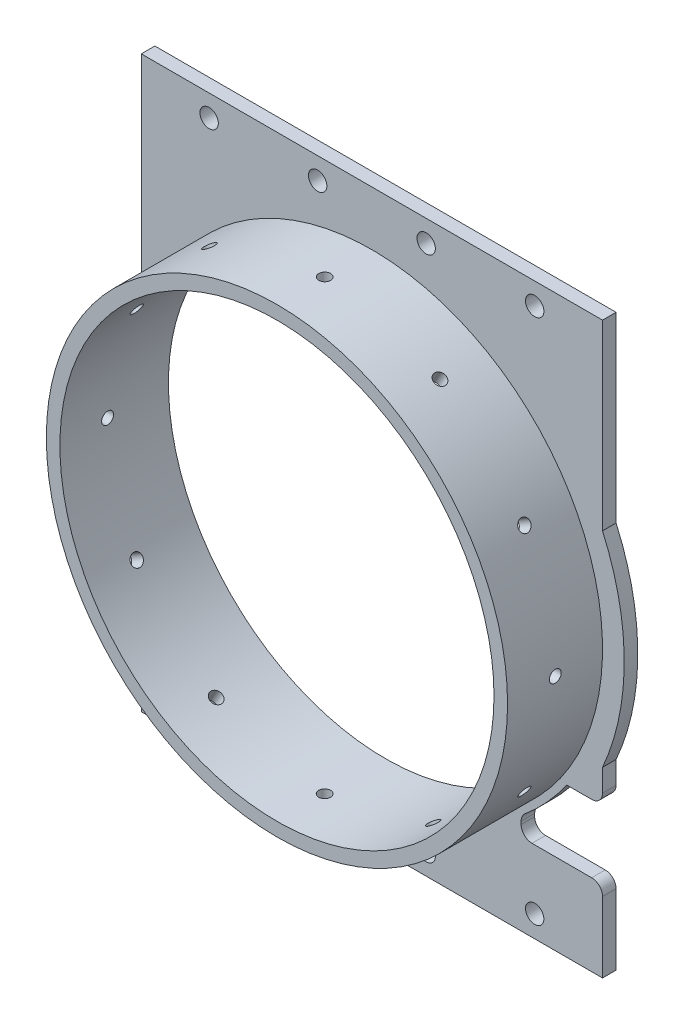
SolidWorks part; units mm, degrees
material "PET"
ref_plane "Front Plane" through (0, 0, 0) normal (0, 0, 1) x (1, 0, 0)
ref_plane "Top Plane" through (0, 0, 0) normal (0, 1, 0) x (1, 0, 0)
ref_plane "Right Plane" through (0, 0, 0) normal (1, 0, 0) x (0, 0, -1)
sketch "Sketch1" plane through (0, 0, 0) normal (0, 0, 1) x (1, 0, 0)
  circle A0 centre (0, 0) radius 50.8
  circle A1 centre (0, 0) radius 53.975
  dimension "D1" = 101.6
  dimension "D2" = 3.175
extrude "Boss-Extrude1" add sketch "Sketch1" along normal blind 25.4
sketch "Sketch2" plane through (0, 0, 0) normal (0, 0, 1) x (1, 0, 0)
  line L0 (-53.975, 0) -> (-53.975, 66.675)
  line L1 (-53.975, 66.675) -> (53.975, 66.675)
  line L2 (53.975, 66.675) -> (53.975, 0)
  line L3 (53.975, 0) -> (53.975, -66.675)
  line L4 (53.975, -66.675) -> (-53.975, -66.675)
  line L5 (-53.975, -66.675) -> (-53.975, 0)
  circle A0 centre (0, 0) radius 53.975 construction
  circle A1 centre (0, 0) radius 50.8 construction
  circle A2 centre (0, 0) radius 50.8
  dimension "D1" = 133.35
extrude "Boss-Extrude2" add sketch "Sketch2" along normal blind 3.175
sketch "Sketch3" plane through (0, 0, 3.175) normal (0, 0, 1) x (1, 0, 0)
  line L0 (53.975, -66.675) -> (53.975, 0) construction
  line L1 (53.975, -47.625) -> (34.925, -47.625)
  line L2 (53.975, -47.625) -> (53.975, -31.75)
  line L5 (45.5975, -31.75) -> (53.975, -31.75)
  line L6 (34.925, -43.2138) -> (34.925, -47.625)
  line L7 (-53.975, -66.675) -> (53.975, -66.675) construction
  arc A0 (45.5975, -31.75) -> (34.925, -43.2138) centre (0, 0) cw
  arc A1 (-53.975, 0) -> (53.975, 0) centre (0, 0) ccw construction
  point P2 (32.8299, -51.5623)
  dimension "D3" = 1.5875
  dimension "D1" = 19.05
  dimension "D2" = 15.875
  dimension "D4" = 19.05
extrude "Cut-Extrude1" cut sketch "Sketch3" against normal through all
sketch "Sketch4" plane through (0, 0, 3.175) normal (0, 0, 1) x (1, 0, 0)
  line L0 (53.975, 0) -> (53.975, 66.675) construction
  line L1 (53.975, -31.75) -> (53.975, 0) construction
  line L2 (53.975, 23.9623) -> (53.975, -23.9623)
  arc A0 (53.975, 23.9623) -> (53.975, -23.9623) centre (0, 0) cw
  arc A1 (-53.975, 0) -> (53.975, 0) centre (0, 0) ccw construction
  dimension "D1" = 5.08
extrude "Boss-Extrude3" add sketch "Sketch4" against normal up to surface (3.175 mm away) up to face at (24.867, -22.4824, 0)
fillet "Fillet1" radius 2.54 4 edges at (53.975, -47.625, 1.5875) (53.975, -31.75, 1.5875) (34.925, -43.2138, 1.5875) (34.925, -47.625, 1.5875)
sketch "Sketch5" plane through (0, 0, 0) normal (0, 1, 0) x (1, 0, 0)
  line L0 (0, -14.2296) -> (0, -3.175) construction
  line L1 (53.975, -3.175) -> (-53.975, -3.175) construction
  line L2 (0, -14.2296) -> (0, -25.2842) construction
  circle A0 centre (0, -14.2296) radius 1.397
  dimension "D1" = 2.794
extrude "Cut-Extrude2" cut sketch "Sketch5" against normal through all both and the other way through all
pattern_circular "CirPattern1" count 7 over 180 about axis through (0, 0, 25.4) along (0, 0, 1) of "Cut-Extrude2"
hole_wizard "#6 Clearance Hole1" positions "Sketch8" profile "Sketch9" hole size "#6" standard "ANSI Inch" end condition through all
sketch "Sketch8" plane through (0, 0, 3.175) normal (0, 0, 1) x (1, 0, 0)
  line L0 (0, 0) -> (0, 66.675) construction
  line L1 (53.975, 66.675) -> (-53.975, 66.675) construction
  point P0 (-38.1, 61.595)
  point P2 (-12.7, 61.595)
  point P4 (12.7, 61.595)
  point P6 (38.1, 61.595)
  point P8 (38.1, -61.595)
  point P10 (12.7, -61.595)
  point P12 (-12.7, -61.595)
  point P14 (-38.1, -61.595)
  dimension "D1" = 25.4
  dimension "D2" = 25.4
  dimension "D3" = 25.4
  dimension "D4" = 123.19
  dimension "D5" = 61.595
sketch "Sketch9" plane through (-38.1, 61.595, 3.175) normal (1, 0, 0) x (0, -1, 0)
  line L0 (0, 0) -> (0, 3.175)
  line L1 (0, 3.175) -> (2.1526, 3.175)
  line L2 (2.1526, 3.175) -> (2.1526, 0)
  line L5 (2.1526, 0) -> (0, 0)
  line L11 (0, -6.35) -> (0, 107.95) construction
  dimension "Thru Hole Dia." = 4.3053
  dimension "Thru Hole Depth" = 3.175
equation "\"D5@Sketch8\"=\"D4@Sketch8\"/2"
